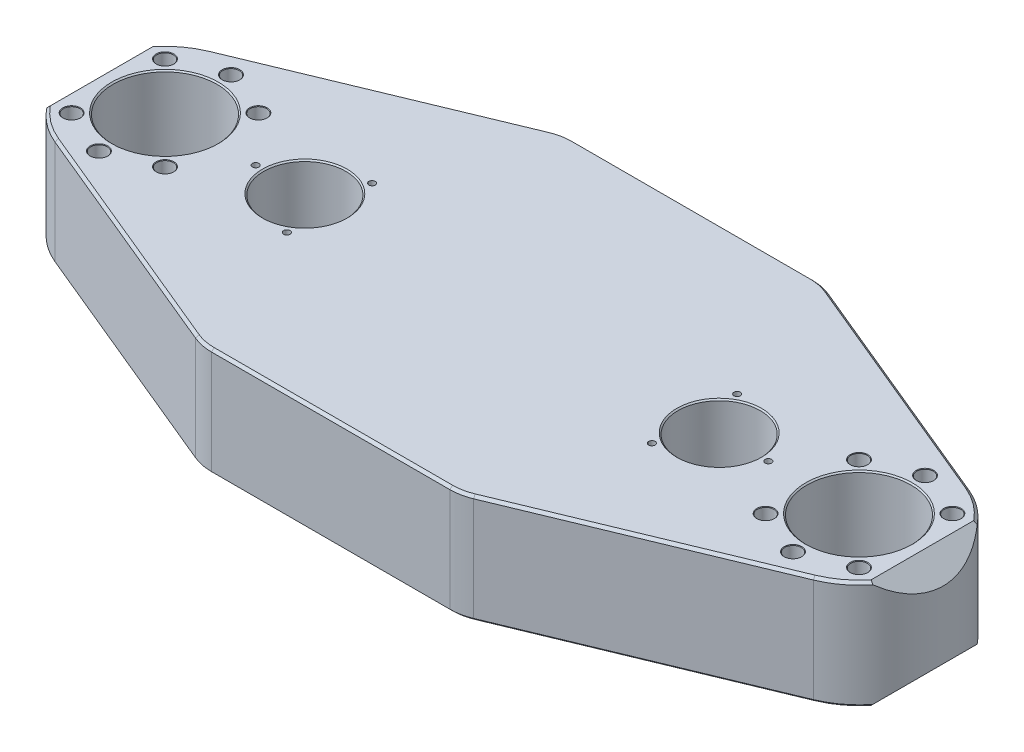
SolidWorks part; units mm, degrees
material "7075-T6 Aluminum"
ref_plane "Front Plane" through (0, 0, 0) normal (0, 0, 1) x (1, 0, 0)
ref_plane "Top Plane" through (0, 0, 0) normal (0, 1, 0) x (1, 0, 0)
ref_plane "Right Plane" through (0, 0, 0) normal (1, 0, 0) x (0, 0, -1)
sketch "Sketch1" plane through (0, 0, 0) normal (0, 1, 0) x (1, 0, 0)
  line L0 (134, 0) -> (0, 0) construction
  line L1 (0, 0) -> (-134, 0) construction
  line L2 (-80, 0) -> (0, 0) construction
  line L3 (0, 0) -> (80, 0) construction
  line L18 (0, 70) -> (0, 0) construction
  line L19 (0, 0) -> (0, -70) construction
  line L20 (-146.4447, 30.023) -> (-53.6774, 68.4757)
  line L21 (-46.0191, 70) -> (46.0191, 70)
  line L22 (53.6774, 68.4757) -> (146.4447, 30.023)
  line L23 (-146.4447, -30.023) -> (-53.6774, -68.4757)
  line L24 (-46.0191, -70) -> (46.0191, -70)
  line L25 (53.6774, -68.4757) -> (146.4447, -30.023)
  circle A0 centre (-134, 0) radius 20.1
  circle A1 centre (134, 0) radius 20.1
  circle A2 centre (-80, 0) radius 15.875
  circle A3 centre (80, 0) radius 15.875
  arc A6 (-53.6774, -68.4757) -> (-46.0191, -70) centre (-46.0191, -50) ccw
  arc A7 (46.0191, -70) -> (53.6774, -68.4757) centre (46.0191, -50) ccw
  arc A8 (-146.4447, 30.023) -> (-146.4447, -30.023) centre (-134, 0) ccw
  arc A9 (146.4447, -30.023) -> (146.4447, 30.023) centre (134, 0) ccw
  arc A10 (46.0191, 70) -> (53.6774, 68.4757) centre (46.0191, 50) cw
  arc A11 (-53.6774, 68.4757) -> (-46.0191, 70) centre (-46.0191, 50) cw
  point P20 (0, 74.2864)
  point P21 (0, 0)
  point P23 (0, 63.5481)
  point P24 (-67.7953, 60)
  point P25 (-61.5447, 70)
  point P30 (-50, -70)
  point P36 (50, 70)
  point P39 (-50, 70)
  dimension "D1" = 40.2
  dimension "D3" = 160
  dimension "D7" = 31.75
  dimension "D8" = 20
  dimension "D6" = 32.5
  dimension "D2" = 268
  dimension "D4" = 140
  dimension "D5" = 100
extrude "Boss-Extrude1" add sketch "Sketch1" along normal mid plane 42
sketch "Sketch3" plane through (0, 0, 0) normal (0, 0, 1) x (1, 0, 0)
  circle A0 centre (0, 0) radius 4
  dimension "D1" = 8
extrude "Cut-Extrude1" [suppressed] cut sketch "Sketch3" against normal through all both and the other way through all
sketch "Sketch4" [suppressed] plane through (0, 20, 0) normal (0, 1, 0) x (1, 0, 0)
  line L0 (108, 0) -> (0, 0) construction
  line L1 (168.7721, -106.7964) -> (108, -106.7964)
  line L2 (168.7721, -106.7964) -> (168.7721, 106.7964)
  line L3 (168.7721, 106.7964) -> (108, 106.7964)
  line L4 (108, -106.7964) -> (108, 106.7964)
  line L5 (168.7721, -106.7964) -> (108, 106.7964) construction
  line L6 (168.7721, 106.7964) -> (108, -106.7964) construction
  line L7 (-196.3958, 92.9845) -> (-108, 92.9845)
  line L8 (-196.3958, 92.9845) -> (-196.3958, -92.9845)
  line L9 (-196.3958, -92.9845) -> (-108, -92.9845)
  line L10 (-108, 92.9845) -> (-108, -92.9845)
  line L11 (-196.3958, 92.9845) -> (-108, -92.9845) construction
  line L12 (-196.3958, -92.9845) -> (-108, 92.9845) construction
  line L13 (0, 0) -> (-108, 0) construction
  point P0 (138.386, 0)
  point P6 (-152.1979, 0)
  dimension "D1" = 216
chamfer "Chamfer1" [suppressed] distance 4 angle 45
sketch "Sketch5" plane through (0, 0, 0) normal (0, 0, 1) x (1, 0, 0)
  line L0 (158.5, -21) -> (166.5, -13)
  line L1 (166.5, -13) -> (166.5, -21)
  line L2 (166.5, -21) -> (158.5, -21)
  dimension "D1" = 45
  dimension "D2" = 8
extrude "Cut-Extrude3" cut sketch "Sketch5" against normal through all both and the other way through all
mirror "Mirror1" about plane through (0, 0, 0) normal (0, 1, 0) of "Cut-Extrude3"
mirror "Mirror2" about plane through (0, 0, 0) normal (1, 0, 0) of "Mirror1", "Cut-Extrude3"
sketch "Sketch6" plane through (0, 21, 0) normal (0, 1, 0) x (1, 0, 0)
  circle A0 centre (0, 35.7714) radius 12.8397
extrude "Cut-Extrude4" [suppressed] cut sketch "Sketch6" against normal blind 14
fillet "Fillet1" [suppressed] radius 10
mirror "Mirror3" [suppressed] about plane through (0, 0, 0) normal (0, 1, 0)
fillet "Fillet2" [suppressed] radius 4
fillet "Fillet3" [suppressed] radius 4
sketch "Sketch7" plane through (0, -21, 0) normal (0, -1, 0) x (1, 0, 0)
  circle A0 centre (115.9688, 18.0312) radius 3.3 construction
  circle A1 centre (134, 25.5) radius 3.3 construction
  circle A2 centre (152.0312, 18.0312) radius 3.3 construction
  circle A3 centre (152.0312, -18.0312) radius 3.3 construction
  circle A4 centre (134, -25.5) radius 3.3 construction
  circle A5 centre (115.9688, -18.0312) radius 3.3 construction
  circle A6 centre (115.9688, 18.0312) radius 3.3
  circle A7 centre (134, 25.5) radius 3.3
  circle A8 centre (152.0312, 18.0312) radius 3.3
  circle A9 centre (152.0312, -18.0312) radius 3.3
  circle A10 centre (134, -25.5) radius 3.3
  circle A11 centre (115.9688, -18.0312) radius 3.3
hole_wizard "M6 Clearance Hole1" positions "Sketch8" profile "Sketch9" hole size "M6" standard "ANSI Metric" end condition through all
sketch "Sketch8" plane through (0, -21, 0) normal (0, -1, 0) x (-1, 0, 0)
  point P0 (-115.9688, -18.0312)
  point P3 (-134, -25.5)
  point P6 (-152.0312, -18.0312)
  point P9 (-152.0312, 18.0312)
  point P12 (-134, 25.5)
  point P15 (-115.9688, 18.0312)
sketch "Sketch9" plane through (115.9688, -21, 18.0312) normal (1, 0, 0) x (0, 0, -1)
  line L0 (0, 0) -> (0, 42)
  line L1 (0, 42) -> (3.2, 42)
  line L2 (3.2, 42) -> (3.2, 0)
  line L5 (3.2, 0) -> (0, 0)
  line L11 (0, -6.35) -> (0, 107.95) construction
  dimension "Thru Hole Dia." = 6.4
  dimension "Thru Hole Depth" = 42
mirror "Mirror5" about plane through (0, 0, 0) normal (1, 0, 0) of "M6 Clearance Hole1"
chamfer "Chamfer2" distance 0.5 angle 45 4 edges at (134, 21, 20.1) (134, -21, 20.1) (-134, -21, 20.1) (-134, 21, 20.1)
chamfer "Chamfer3" [suppressed] distance 1 angle 45
chamfer "Chamfer4" [suppressed] distance 0.2 angle 45
chamfer "Chamfer5" distance 1 angle 45 28 edges at (152.9741, -21, -26.3863) (-152.9741, -21, -26.3863) (100.0611, -21, -49.2493) (-100.0611, -21, -49.2493) (49.9234, -21, -69.6152) (-49.9234, -21, -69.6152) (0, -21, -70) (-152.9741, -21, 26.3863) (152.9741, -21, 26.3863) (-100.0611, -21, 49.2493) (100.0611, -21, 49.2493) (-49.9234, -21, 69.6152) (49.9234, -21, 69.6152) (0, -21, 70) (152.9741, 21, -26.3863) (-152.9741, 21, -26.3863) (100.0611, 21, -49.2493) (-100.0611, 21, -49.2493) (49.9234, 21, -69.6152) (-49.9234, 21, -69.6152) (0, 21, -70) (-152.9741, 21, 26.3863) (152.9741, 21, 26.3863) (-100.0611, 21, 49.2493) (100.0611, 21, 49.2493) (-49.9234, 21, 69.6152) (49.9234, 21, 69.6152) (0, 21, 70)
chamfer "Chamfer6" distance 0.5 angle 45 4 edges at (80, -21, 15.875) (80, 21, 15.875) (-80, -21, 15.875) (-80, 21, 15.875)
sketch "Sketch10" plane through (0, 21, 0) normal (0, 1, 0) x (1, 0, 0)
  line L0 (70.5, -16.4545) -> (70.5, 16.4545) construction
  line L1 (70.5, 16.4545) -> (99, 0) construction
  line L2 (99, 0) -> (70.5, -16.4545) construction
  circle A3 centre (70.5, -16.4545) radius 1.7
  circle A4 centre (70.5, 16.4545) radius 1.7
  circle A5 centre (99, 0) radius 1.7
  circle A6 centre (80, 0) radius 19 construction
  dimension "D1" = 38
hole_wizard "M3x0.5 Tapped Hole1" positions "Sketch11" profile "Sketch13" tap size "M3x0.5" standard "ANSI Metric"
sketch "Sketch11" plane through (0, 21, 0) normal (0, 1, 0) x (1, 0, 0)
  point P0 (99, 0)
  point P3 (70.5, -16.4545)
  point P6 (70.5, 16.4545)
sketch "Sketch13" plane through (99, 21, 0) normal (1, 0, 0) x (0, 0, 1)
  line L0 (0, 0) -> (0, 8.2511)
  line L1 (0, 8.2511) -> (1.25, 7.5)
  line L2 (1.25, 7.5) -> (1.25, 0)
  line L5 (1.25, 0) -> (0, 0)
  line L10 (0, 8.2511) -> (-1.25, 7.5) construction
  line L11 (0, -6.35) -> (0, 107.95) construction
  dimension "Tap Drill Dia." = 2.5
  dimension "Tap Drill Depth" = 7.5
  dimension "Drill Angle" = 118
cosmetic thread "Hole Thread9" parameters "D1"=6, "D2"=3
cosmetic thread "Hole Thread13" parameters "D1"=6, "D2"=3
cosmetic thread "Hole Thread14" parameters "D1"=6, "D2"=3
mirror "Mirror6" about plane through (0, 0, 0) normal (1, 0, 0) of "M3x0.5 Tapped Hole1"
mirror "Mirror7" about plane through (0, 0, 0) normal (0, 1, 0) of "Mirror6", "M3x0.5 Tapped Hole1"
sketch "Sketch14" plane through (0, -21, 0) normal (0, -1, 0) x (1, 0, 0)
  circle A0 centre (-102.1222, -29) radius 3.25 construction
  circle A1 centre (-102.1222, -29) radius 3.25
hole_wizard "M6x1.0 Tapped Hole1" [suppressed] positions "Sketch15" profile "Sketch17" tap size "M6x1.0" standard "ANSI Metric"
sketch "Sketch15" plane through (0, -21, 0) normal (0, -1, 0) x (-1, 0, 0)
  point P0 (0, 29)
sketch "Sketch17" plane through (0, -21, -29) normal (1, 0, 0) x (0, 0, -1)
  line L0 (0, 0) -> (0, 11.5022)
  line L1 (0, 11.5022) -> (2.5, 10)
  line L2 (2.5, 10) -> (2.5, 0)
  line L5 (2.5, 0) -> (0, 0)
  line L10 (0, 11.5022) -> (-2.5, 10) construction
  line L11 (0, -6.35) -> (0, 107.95) construction
  dimension "Tap Drill Dia." = 5
  dimension "Tap Drill Depth" = 10
  dimension "Drill Angle" = 118
cosmetic thread "Hole Thread10" [suppressed] parameters "D1"=8, "D2"=6
chamfer "Chamfer8" [suppressed] distance 0.3 angle 45
chamfer "Chamfer9" distance 0.2 angle 45 24 edges at (-152.0312, -21, -21.2312) (-152.0312, 21, -21.2312) (-134, -21, -28.7) (-134, 21, -28.7) (-115.9688, -21, -21.2312) (-115.9688, 21, -21.2312) (-115.9688, -21, 14.8312) (-115.9688, 21, 14.8312) (-134, -21, 22.3) (-134, 21, 22.3) (-152.0312, -21, 14.8312) (-152.0312, 21, 14.8312) (152.0312, -21, 14.8312) (152.0312, 21, 14.8312) (134, -21, 22.3) (134, 21, 22.3) (115.9688, -21, 14.8312) (115.9688, 21, 14.8312) (115.9688, -21, -21.2312) (115.9688, 21, -21.2312) (152.0312, -21, -21.2312) (152.0312, 21, -21.2312) (134, -21, -28.7) (134, 21, -28.7)
